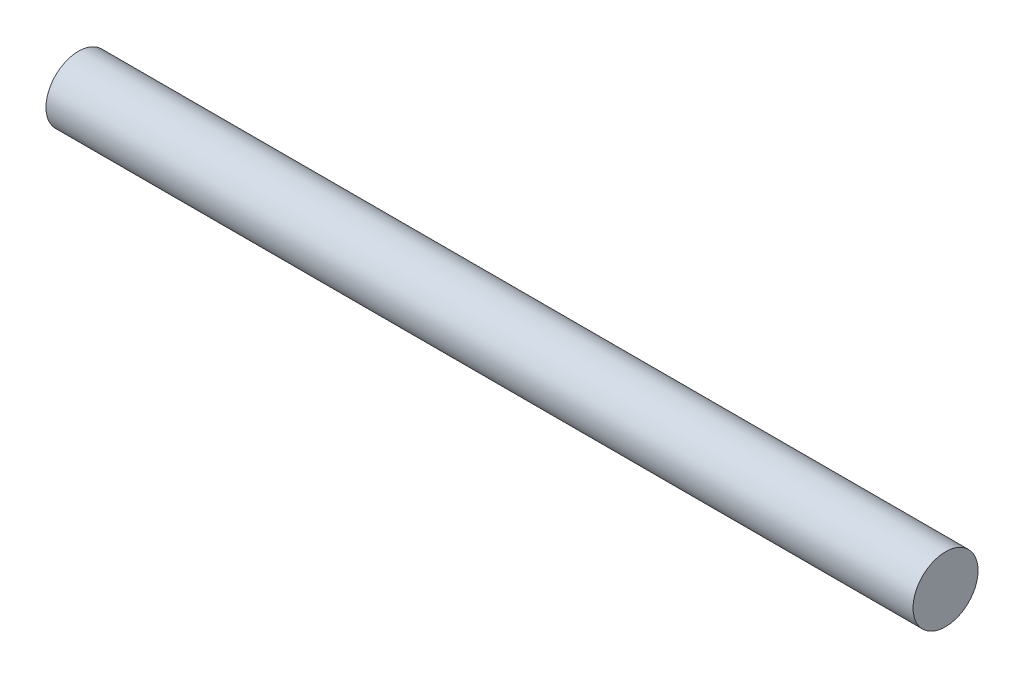
SolidWorks part; units mm, degrees
ref_plane "Front" through (0, 0, 0) normal (0, 0, 1) x (1, 0, 0)
ref_plane "Top" through (0, 0, 0) normal (0, 1, 0) x (1, 0, 0)
ref_plane "Right" through (0, 0, 0) normal (1, 0, 0) x (0, 0, -1)
sketch "Эскиз1" plane through (0, 0, 0) normal (0, 0, 1) x (1, 0, 0)
  line L0 (0, 0) -> (36.9802, 0) construction
  line L2 (0, 0) -> (40, 0)
  line L3 (0, 0) -> (0, 1.5)
  line L4 (0, 1.5) -> (40, 1.5)
  line L5 (40, 0) -> (40, 1.5)
  dimension "D1" = 40
  dimension "D2" = 1.5
revolve "Повернуть1" add sketch "Эскиз1" angle 360 about L0
